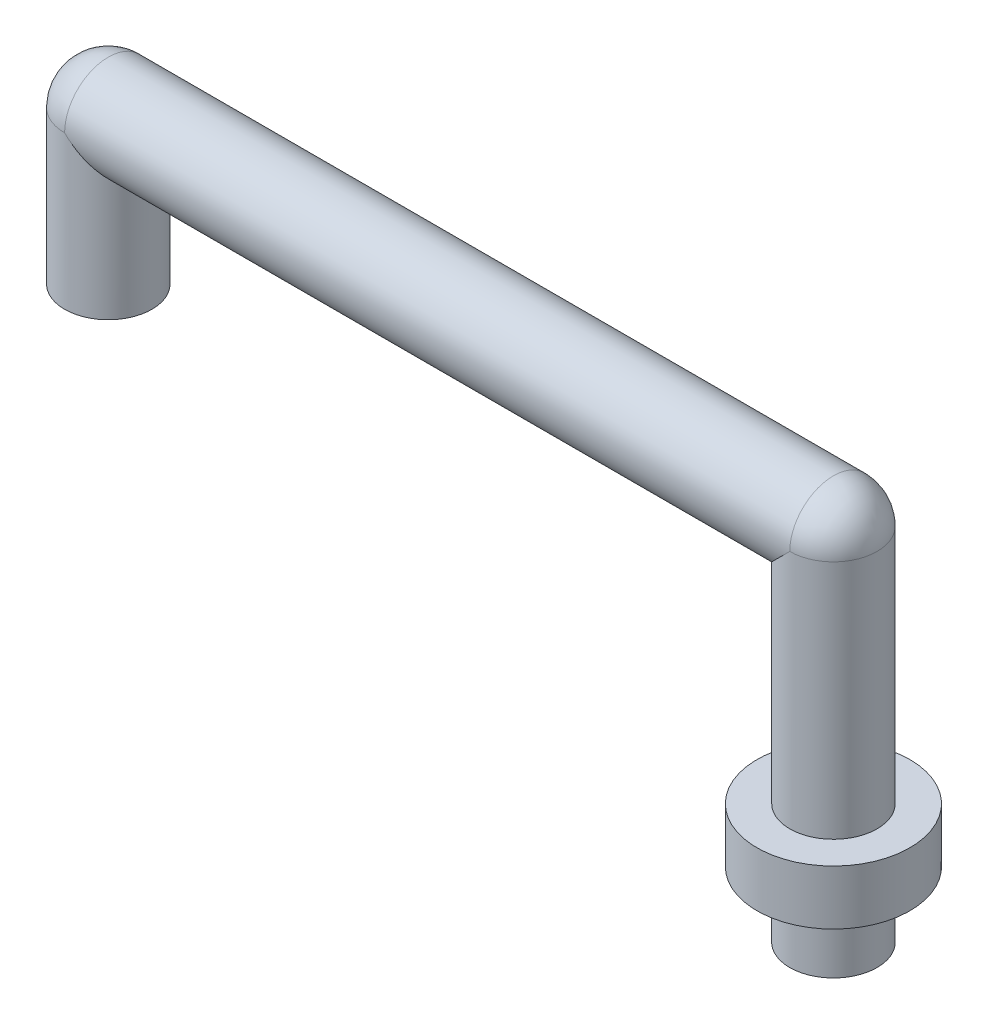
SolidWorks part; units mm, degrees
ref_plane "Front Plane" through (0, 0, 0) normal (0, 0, 1) x (1, 0, 0)
ref_plane "Top Plane" through (0, 0, 0) normal (0, 1, 0) x (1, 0, 0)
ref_plane "Right Plane" through (0, 0, 0) normal (1, 0, 0) x (0, 0, -1)
sketch "Sketch2" plane through (0, 0, 0) normal (0, 1, 0) x (-1, 0, 0)
  circle A0 centre (0, 0) radius 5.08
  dimension "D1" = 10.16
extrude "Boss-Extrude2" add sketch "Sketch2" along normal blind 41.91
sketch "Sketch3" plane through (0, 0, 0) normal (0, 0, 1) x (1, 0, 0)
  line L1 (0, 0) -> (0, 7.62) construction
  line L4 (0, 7.62) -> (0, 13.97)
  line L7 (0, 7.62) -> (-8.89, 7.62)
  line L8 (-8.89, 7.62) -> (-8.89, 13.97)
  line L9 (-8.89, 13.97) -> (0, 13.97)
  dimension "D1" = 6.35
  dimension "D2" = 8.89
  dimension "D3" = 7.62
revolve "Revolve1" add sketch "Sketch3" angle 360 about L1
sketch "Sketch4" plane through (0, 41.91, 0) normal (0, 1, 0) x (1, 0, 0)
  line L0 (0, 5.08) -> (0, -5.08) construction
  line L1 (-5.08, 0) -> (5.08, 0) construction
  line L2 (0, 5.08) -> (-84.328, 5.08)
  line L3 (-84.328, 5.08) -> (-84.328, 0)
  line L4 (-84.328, 0) -> (5.08, 0)
  arc A2 (5.08, 0) -> (0, 5.08) centre (0, 0) ccw
  dimension "D1" = 10.16
  dimension "D2" = 84.328
revolve "Revolve2" add sketch "Sketch4" angle 360 about L4
sketch "Sketch5" plane through (-84.328, 0, 0) normal (-1, 0, 0) x (0, 0, 1)
  line L0 (0, 46.99) -> (0, 24.13)
  line L1 (-5.08, 41.91) -> (5.08, 41.91) construction
  line L2 (-5.08, 41.91) -> (-5.08, 24.13)
  line L3 (-5.08, 24.13) -> (0, 24.13)
  arc A0 (0, 46.99) -> (-5.08, 41.91) centre (0, 41.91) ccw
  circle A1 centre (0, 41.91) radius 5.08 construction
  dimension "D1" = 22.86
revolve "Revolve3" add sketch "Sketch5" angle 360 about L0
sketch "Sketch6" plane through (0, 24.13, 0) normal (0, -1, 0) x (1, 0, 0)
  circle A0 centre (-84.328, 0) radius 2.54
  dimension "D1" = 5.08
extrude "Cut-Extrude1" cut sketch "Sketch6" against normal blind 17.78 contours A0
sketch "Sketch7" plane through (0, 0, 0) normal (0, -1, 0) x (1, 0, 0)
  circle A0 centre (0, 0) radius 2.54
  dimension "D1" = 5.08
extrude "Cut-Extrude2" cut sketch "Sketch7" against normal blind 19.05
